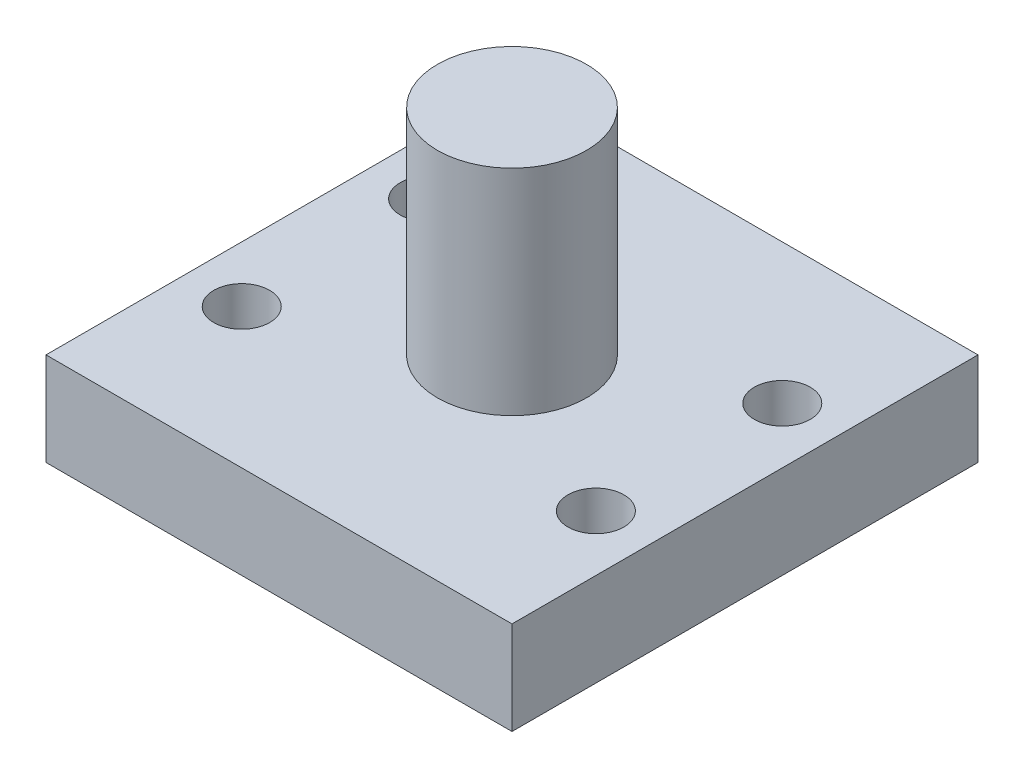
SolidWorks part; units mm, degrees
ref_plane "前视基准面" through (0, 0, 0) normal (0, 0, 1) x (1, 0, 0)
ref_plane "上视基准面" through (0, 0, 0) normal (0, 1, 0) x (1, 0, 0)
ref_plane "右视基准面" through (0, 0, 0) normal (1, 0, 0) x (0, 0, -1)
sketch "草图1" plane through (0, 0, 0) normal (0, 1, 0) x (1, 0, 0)
  circle A0 centre (0, 0) radius 4
  dimension "D1" = 8
extrude "凸台-拉伸1" add sketch "草图1" along normal blind 11.5
sketch "草图2" plane through (0, 0, 0) normal (0, 0, 1) x (1, 0, 0)
  circle A0 centre (0, 3) radius 2
  dimension "D1" = 4
  dimension "D2" = 3
sketch "草图3" plane through (0, 0, 0) normal (0, -1, 0) x (1, 0, 0)
  line L1 (-12.5, -12.5) -> (12.5, -12.5)
  line L2 (-12.5, -12.5) -> (-12.5, 12.5)
  line L3 (-12.5, 12.5) -> (12.5, 12.5)
  line L4 (12.5, -12.5) -> (12.5, 12.5)
  line L5 (-12.5, -12.5) -> (12.5, 12.5) construction
  line L6 (-12.5, 12.5) -> (12.5, -12.5) construction
  point P0 (0, 0)
  dimension "D1" = 25
  dimension "D2" = 25
extrude "凸台-拉伸2" add sketch "草图3" along normal blind 5
sketch "草图4" plane through (0, 0, 0) normal (0, 1, 0) x (1, 0, 0)
  circle A0 centre (9.5, 5) radius 1.5
  circle A4 centre (9.5, -5) radius 1.5
  circle A5 centre (-9.5, -5) radius 1.5
  circle A6 centre (-9.5, 5) radius 1.5
  dimension "D2" = 3
  dimension "D5" = 3
  dimension "D10" = 3
  dimension "D11" = 3
  dimension "D1" = 5
  dimension "D3" = 9.5
  dimension "D4" = 10
  dimension "D6" = 9.5
  dimension "D7" = 19
  dimension "D8" = 10
  dimension "D9" = 19
  dimension "D12" = 5
extrude "切除-拉伸2" cut sketch "草图4" against normal blind 5
